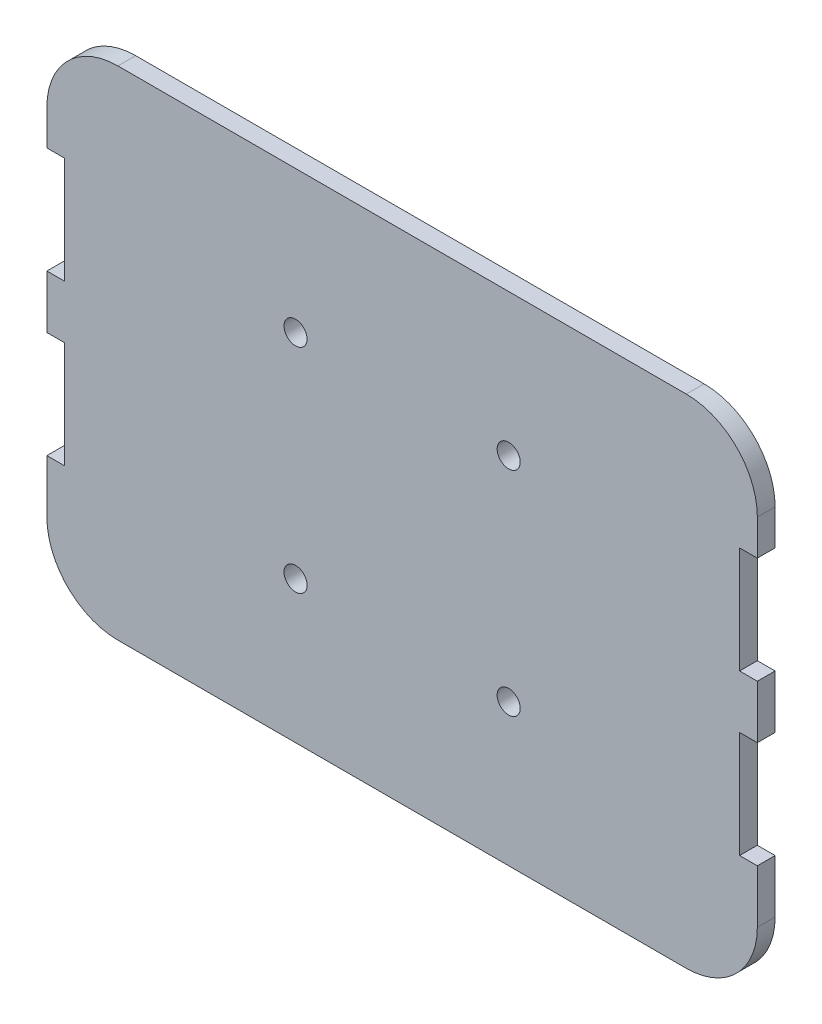
SolidWorks part; units mm, degrees
material "Hexcel AS4C (3000 丝)"
ref_plane "前视基准面" through (0, 0, 0) normal (0, 0, 1) x (1, 0, 0)
ref_plane "上视基准面" through (0, 0, 0) normal (0, 1, 0) x (1, 0, 0)
ref_plane "右视基准面" through (0, 0, 0) normal (1, 0, 0) x (0, 0, -1)
other "Configuration Table"
sketch "草图1" plane through (0, 0, 0) normal (0, 0, 1) x (1, 0, 0)
  line L0 (0, 0) -> (284.1069, 0) construction
  line L1 (-100, 120) -> (100, 120)
  line L2 (-100, 120) -> (-100, -20)
  line L3 (-100, -20) -> (100, -20)
  line L4 (100, 120) -> (100, -20)
  line L5 (0, 0) -> (0, 194.938) construction
  circle A0 centre (30, 80) radius 3.25
  circle A1 centre (30, 20) radius 3.25
  circle A2 centre (-30, 80) radius 3.25
  circle A3 centre (-30, 20) radius 3.25
  point P16 (0, 0)
  point P17 (30, -30)
  point P18 (30, 71.9337)
  point P19 (0, 0)
  point P20 (0, 0)
  point P21 (30, 20)
  dimension "D3" = 6.5
  dimension "D6" = 40
  dimension "D1" = 120
  dimension "D2" = 200
  dimension "D4" = 30
  dimension "D5" = 60
  dimension "D7" = 20
extrude "凸台-拉伸1" add sketch "草图1" along normal blind 5
fillet "圆角1" radius 20 4 edges at (-100, 120, 2.5) (-100, -20, 2.5) (100, -20, 2.5) (100, 120, 2.5)
sketch "草图3" plane through (0, 0, 5) normal (0, 0, 1) x (1, 0, 0)
  line L0 (0, 126.8429) -> (0, -134.2378) construction
  line L1 (-131.0539, 0) -> (117.702, 0) construction
  line L2 (100, 100) -> (100, 0) construction
  line L3 (95, 90) -> (100, 90)
  line L4 (95, 90) -> (95, 60)
  line L5 (95, 60) -> (100, 60)
  line L6 (100, 90) -> (100, 60)
  line L8 (95, 45) -> (100, 45)
  line L9 (95, 45) -> (95, 15)
  line L10 (95, 15) -> (100, 15)
  line L11 (100, 45) -> (100, 15)
  line L26 (-100, 45) -> (-100, 15)
  line L27 (-95, 15) -> (-100, 15)
  line L28 (-95, 45) -> (-95, 15)
  line L29 (-95, 45) -> (-100, 45)
  line L31 (-100, 90) -> (-100, 60)
  line L32 (-95, 60) -> (-100, 60)
  line L33 (-95, 90) -> (-95, 60)
  line L34 (-95, 90) -> (-100, 90)
  dimension "D1" = 5
  dimension "D2" = 5
  dimension "D3" = 15
  dimension "D4" = 30
  dimension "D5" = 15
  dimension "D6" = 30
extrude "切除-拉伸1" cut sketch "草图3" against normal blind 39
